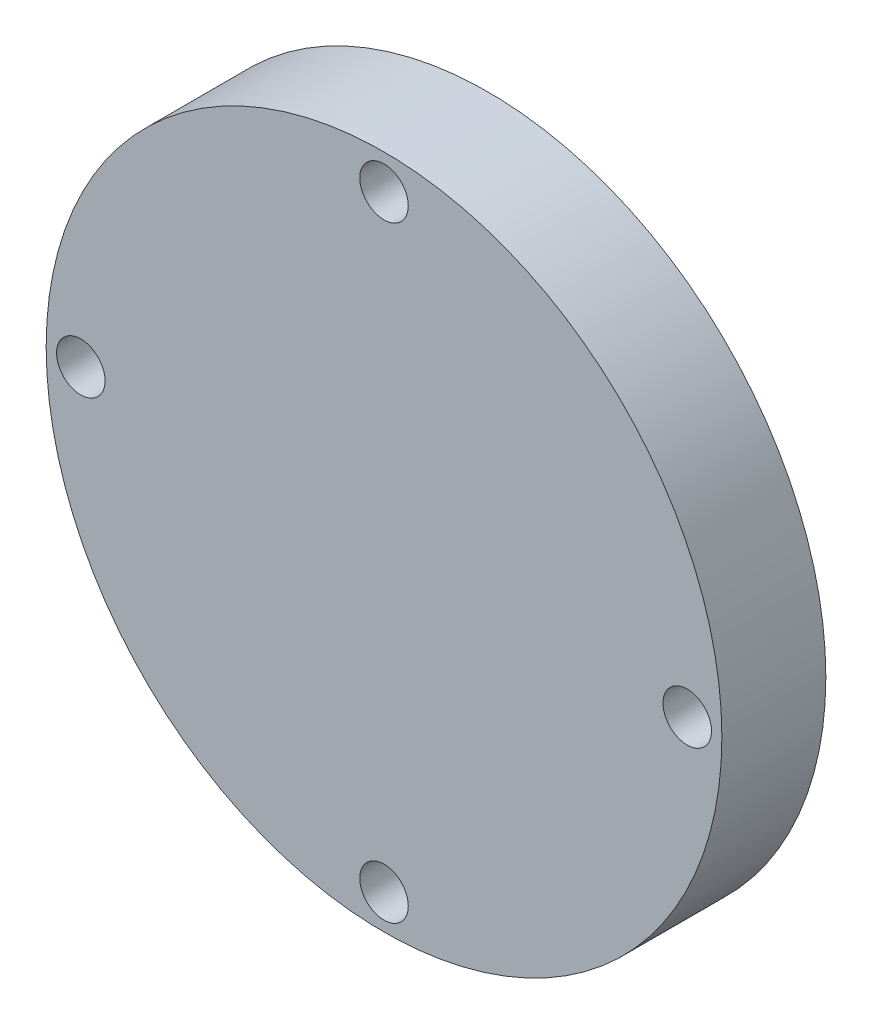
SolidWorks part; units mm, degrees
ref_plane "Front Plane" through (0, 0, 0) normal (0, 0, 1) x (1, 0, 0)
ref_plane "Top Plane" through (0, 0, 0) normal (0, 1, 0) x (1, 0, 0)
ref_plane "Right Plane" through (0, 0, 0) normal (1, 0, 0) x (0, 0, -1)
sketch "Sketch1" plane through (0, 0, 0) normal (0, 0, 1) x (1, 0, 0)
  circle A2 centre (8.3973, 31.4947) radius 19.5
  circle A6 centre (25.8973, 31.4947) radius 1.4
  circle A7 centre (8.3973, 13.9947) radius 1.4
  circle A8 centre (-9.1027, 31.4947) radius 1.4
  circle A9 centre (8.3973, 48.9947) radius 1.4
extrude "Boss-Extrude1" add sketch "Sketch1" along normal blind 6 contours A2 A9 A8 A7 A6
